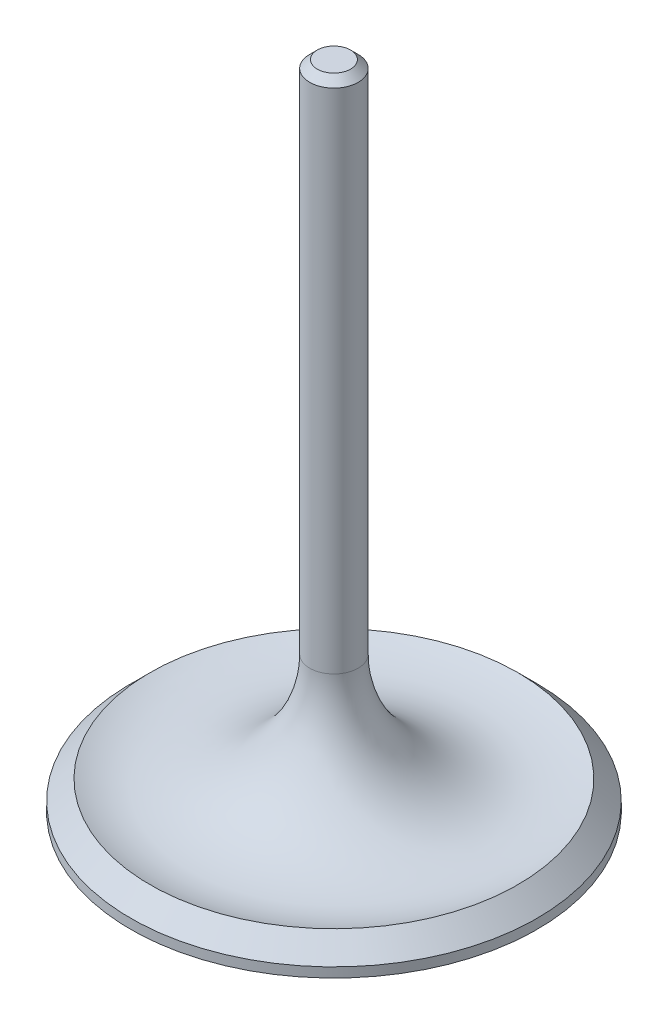
SolidWorks part; units mm, degrees
ref_plane "Front Plane" through (0, 0, 0) normal (0, 0, 1) x (1, 0, 0)
ref_plane "Top Plane" through (0, 0, 0) normal (0, 1, 0) x (1, 0, 0)
ref_plane "Right Plane" through (0, 0, 0) normal (1, 0, 0) x (0, 0, -1)
sketch "Sketch1" plane through (0, 0, 0) normal (0, 0, 1) x (1, 0, 0)
  line L0 (0, 0) -> (0, 85.55)
  line L1 (0, 85.55) -> (3.18, 85.55)
  line L2 (3.18, 85.55) -> (3.18, 17.9547)
  line L3 (24.13, 3.81) -> (26.67, 1.27)
  line L4 (26.67, 1.27) -> (26.67, 0)
  line L5 (26.67, 0) -> (0, 0)
  arc A0 (3.18, 17.9547) -> (24.13, 3.81) centre (18.43, 17.9547) ccw
  dimension "D1" = 85.55
  dimension "D7" = 15.25
  dimension "D2" = 26.67
  dimension "D3" = 3.18
  dimension "D4" = 1.27
  dimension "D5" = 3.81
  dimension "D6" = 45
revolve "Revolve1" add sketch "Sketch1" angle 360 about L0
chamfer "Chamfer1" distance 1 angle 45 1 edges at (0, 85.55, -3.18)
